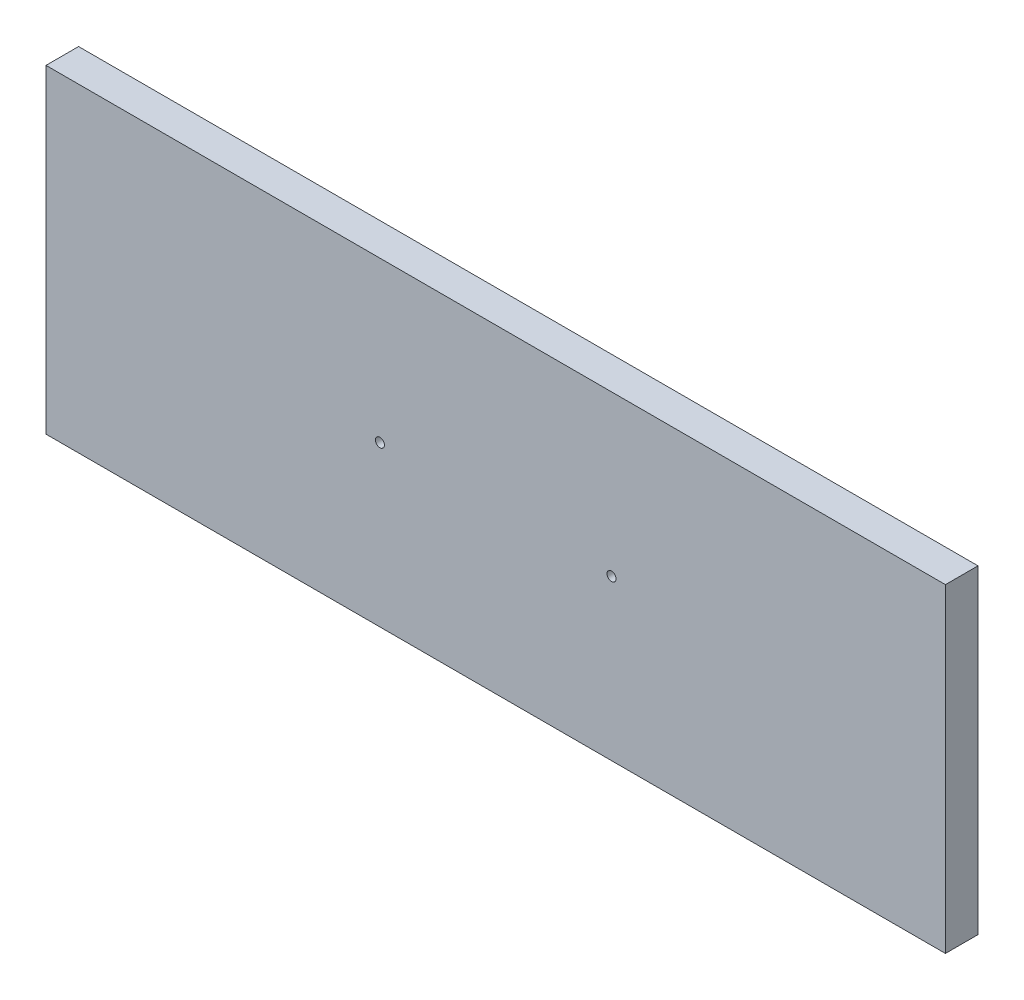
SolidWorks part; units mm, degrees
ref_plane "Front Plane" through (0, 0, 0) normal (0, 0, 1) x (1, 0, 0)
ref_plane "Top Plane" through (0, 0, 0) normal (0, 1, 0) x (1, 0, 0)
ref_plane "Right Plane" through (0, 0, 0) normal (1, 0, 0) x (0, 0, -1)
sketch "Sketch1" plane through (0, 0, 0) normal (0, 0, 1) x (1, 0, 0)
  line L4 (248.5, -394) -> (-248.5, -394)
  line L5 (-248.5, -394) -> (-248.5, -570.5)
  line L6 (-248.5, -570.5) -> (248.5, -570.5)
  line L7 (248.5, -570.5) -> (248.5, -394)
  line L8 (248.5, -394) -> (-248.5, -394)
  line L9 (-248.5, -394) -> (-248.5, -570.5)
  line L10 (-248.5, -570.5) -> (248.5, -570.5)
  line L11 (248.5, -570.5) -> (248.5, -394)
  circle A1 centre (64, -482.25) radius 2.5
  circle A2 centre (64, -482.25) radius 2.5
  circle A3 centre (-64, -482.25) radius 2.5
  circle A4 centre (-64, -482.25) radius 2.5
  dimension "D4" = 497
  dimension "D5" = 176.5
  dimension "D1" = 0
  dimension "D2" = 0
  dimension "D3" = 0
extrude "Boss-Extrude1" add sketch "Sketch1" along normal blind 18
extrude "Cut-Extrude1" cut sketch "Sketch2" against normal blind 13
sketch "Sketch2" plane through (0, 0, 0) normal (0, 0, -1) x (-1, 0, 0)
  line L0 (0, -394) -> (0, -570.5) construction
  line L5 (224, -514) -> (224, -450) construction
  line L6 (-224, -514) -> (-224, -450) construction
  circle A0 centre (224, -514) radius 5
  circle A1 centre (-224, -514) radius 5
  circle A2 centre (224, -450) radius 5
  circle A3 centre (-224, -450) radius 5
  point P6 (216.5, -554.5)
  point P7 (-216.5, -554.5)
